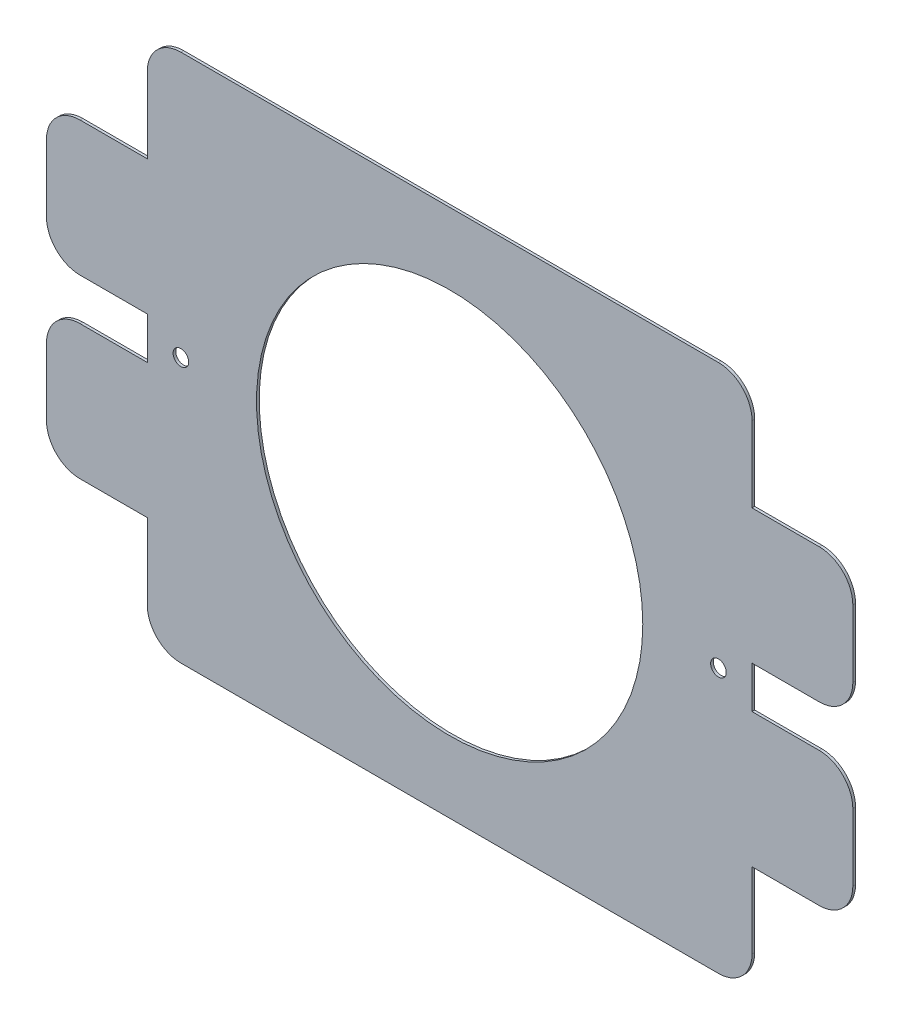
SolidWorks part; units mm, degrees
ref_plane "Front Plane" through (0, 0, 0) normal (0, 0, 1) x (1, 0, 0)
ref_plane "Top Plane" through (0, 0, 0) normal (0, 1, 0) x (1, 0, 0)
ref_plane "Right Plane" through (0, 0, 0) normal (1, 0, 0) x (0, 0, -1)
sketch "Sketch2" plane through (0, 0, 0) normal (0, 0, 1) x (1, 0, 0)
  line L0 (-25, 25) -> (25, 25) construction
  line L1 (0, 36.5) -> (0, -50) construction
  line L2 (-50.8, 0) -> (0, 0) construction
  line L3 (-57.15, 50) -> (57.15, 50)
  line L4 (-57.15, 50) -> (-57.15, -50)
  line L5 (-57.15, -50) -> (57.15, -50)
  line L6 (57.15, 50) -> (57.15, -50)
  line L7 (-57.15, 50) -> (57.15, -50) construction
  line L8 (-57.15, -50) -> (57.15, 50) construction
  line L9 (0, 0) -> (50.8, 0) construction
  line L10 (25, 25) -> (25, -25) construction
  line L11 (25, -25) -> (-25, -25) construction
  line L12 (-25, -25) -> (-25, 25) construction
  line L14 (57.15, 29.3667) -> (76.2, 29.3667)
  line L15 (57.15, 29.3667) -> (57.15, 3.9667)
  line L16 (57.15, 3.9667) -> (76.2, 3.9667)
  line L17 (76.2, 29.3667) -> (76.2, 3.9667)
  line L18 (57.15, -3.9667) -> (76.2, -3.9667)
  line L19 (57.15, -3.9667) -> (57.15, -29.3667)
  line L20 (57.15, -29.3667) -> (76.2, -29.3667)
  line L21 (76.2, -3.9667) -> (76.2, -29.3667)
  line L22 (-57.15, 29.3667) -> (-76.2, 29.3667)
  line L23 (-57.15, 29.3667) -> (-57.15, 3.9667)
  line L24 (-57.15, 3.9667) -> (-76.2, 3.9667)
  line L25 (-76.2, 29.3667) -> (-76.2, 3.9667)
  line L26 (-57.15, -3.9667) -> (-76.2, -3.9667)
  line L27 (-57.15, -3.9667) -> (-57.15, -29.3667)
  line L28 (-57.15, -29.3667) -> (-76.2, -29.3667)
  line L29 (-76.2, -3.9667) -> (-76.2, -29.3667)
  circle A0 centre (0, 0) radius 36.5
  circle A11 centre (-50.8, 0) radius 1.475
  circle A12 centre (50.8, 0) radius 1.475
  point P16 (0, 25)
  point P17 (25, 0)
  point P35 (-76.2, 16.6667)
  point P36 (-76.2, -16.6667)
  point P37 (-82.55, -7.4615)
  dimension "D1" = 73
  dimension "D11" = 2.95
  dimension "D3" = 114.3
  dimension "D10" = 100
  dimension "D12" = 50.8
  dimension "D2" = 50
  dimension "D4" = 33.3333
  dimension "D5" = 33.3333
  dimension "D6" = 19.05
  dimension "D7" = 25.4
extrude "Boss-Extrude1" add sketch "Sketch2" along normal blind 0.508 contours L6 L3 L4 L5 A12 A11 A0 | L22 L25 L24 L4 | L26 L29 L28 L4 | L17 L14 L6 L16 | L21 L18 L6 L20
fillet "Fillet1" radius 6.35 12 edges at (76.2, 29.3667, 0.254) (76.2, 3.9667, 0.254) (76.2, -3.9667, 0.254) (76.2, -29.3667, 0.254) (57.15, -50, 0.254) (-57.15, -50, 0.254) (-76.2, -29.3667, 0.254) (-76.2, -3.9667, 0.254) (-76.2, 3.9667, 0.254) (-76.2, 29.3667, 0.254) (-57.15, 50, 0.254) (57.15, 50, 0.254)
equation "\"D5@Sketch2\"=\"D4@Sketch2\""
